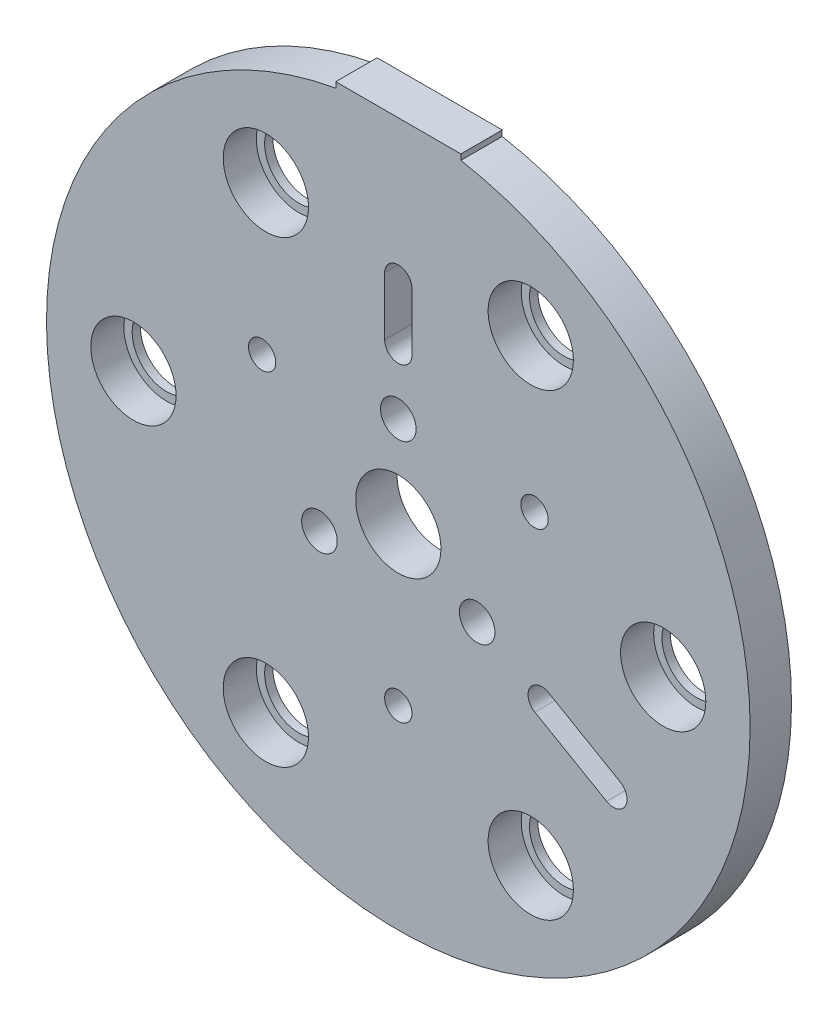
SolidWorks part; units mm, degrees
other "细节项目1"
other "细节项目2"
other "细节项目3"
ref_plane "前视基准面" through (0, 0, 0) normal (0, 0, 1) x (1, 0, 0)
ref_plane "上视基准面" through (0, 0, 0) normal (0, 1, 0) x (1, 0, 0)
ref_plane "右视基准面" through (0, 0, 0) normal (1, 0, 0) x (0, 0, -1)
other "Configuration Table"
sketch "草图1" plane through (0, 0, 0) normal (0, 0, 1) x (1, 0, 0)
  circle A0 centre (0, 0) radius 42.5
  point P0 (0, 0)
  point P19 (0, 0)
  dimension "D1" = 85
extrude "凸台-拉伸1" add sketch "草图1" against normal blind 5 contours A0
sketch "草图2" plane through (0, 0, 0) normal (0, 0, 1) x (1, 0, 0)
  line L0 (0, 0) -> (-32, 0) construction
  circle A1 centre (-32, 0) radius 5.15
  circle A2 centre (-16, 27.7128) radius 5.15
  circle A3 centre (16, 27.7128) radius 5.15
  circle A4 centre (32, 0) radius 5.15
  circle A5 centre (16, -27.7128) radius 5.15
  circle A6 centre (-16, -27.7128) radius 5.15
  point P17 (0, 0)
  dimension "D4" = 10.3
  dimension "D2" = 32
  dimension "D3" = 6
extrude "切除-拉伸1" cut sketch "草图2" against normal through all
sketch "草图3" plane through (0, 0, 0) normal (0, 0, 1) x (1, 0, 0)
  circle A0 centre (0, 0) radius 5.15
  dimension "D1" = 10.3
extrude "切除-拉伸2" cut sketch "草图3" against normal through all
sketch "草图4" plane through (0, 0, -5) normal (0, 0, -1) x (-1, 0, 0)
  circle A0 centre (-16, 27.7128) radius 5.15 construction
  circle A1 centre (-16, 27.7128) radius 5.15
  circle A2 centre (16, 27.7128) radius 5.15 construction
  circle A3 centre (16, 27.7128) radius 5.15
  circle A4 centre (32, 0) radius 5.15 construction
  circle A5 centre (32, 0) radius 5.15
  circle A6 centre (16, -27.7128) radius 5.15 construction
  circle A7 centre (16, -27.7128) radius 5.15
  circle A8 centre (-16, -27.7128) radius 5.15 construction
  circle A9 centre (-16, -27.7128) radius 5.15
  circle A10 centre (-32, 0) radius 5.15 construction
  circle A11 centre (-32, 0) radius 5.15
extrude "拉伸-薄壁1" add sketch "草图4" against normal blind 1 thin thin type one direction reverse wall 1
sketch "草图5" plane through (0, 0, -5) normal (0, 0, -1) x (-1, 0, 0)
  line L0 (0, 0) -> (-42.5, 0) construction
  line L1 (0, 0) -> (-36.8061, 21.25) construction
  circle A0 centre (0, 0) radius 42.5 construction
  circle A1 centre (-16.4545, 9.5) radius 1.65
  circle A2 centre (16.4545, 9.5) radius 1.65
  circle A3 centre (0, -19) radius 1.65
  point P16 (0, 0)
  dimension "D2" = 3.3
  dimension "D1" = 30
  dimension "D4" = 19
  dimension "D3" = 3
extrude "切除-拉伸3" cut sketch "草图5" against normal up to next
sketch "草图7" plane through (0, 0, -5) normal (0, 0, -1) x (-1, 0, 0)
  line L0 (0, 0) -> (-36.8061, -21.25) construction
  line L1 (-17.3205, -10) -> (-25.9808, -15) construction
  line L2 (-16.4955, -11.4289) -> (-25.1558, -16.4289)
  line L3 (-18.1455, -8.5711) -> (-26.8058, -13.5711)
  line L4 (0, 0) -> (-42.5, 0) construction
  circle A0 centre (0, 0) radius 42.5 construction
  arc A1 (-16.4955, -11.4289) -> (-18.1455, -8.5711) centre (-17.3205, -10) ccw
  arc A2 (-26.8058, -13.5711) -> (-25.1558, -16.4289) centre (-25.9808, -15) ccw
  point P8 (-21.6506, -12.5)
  dimension "D1" = 1.65
  dimension "D3" = 30
  dimension "D2" = 10
  dimension "D4" = 30
extrude "切除-拉伸4" cut sketch "草图7" against normal up to next
sketch "草图8" plane through (0, 0, 0) normal (0, 0, 1) x (1, 0, 0)
  line L0 (0, 0) -> (36.8061, -21.25) construction
  line L1 (18.1455, -8.5711) -> (26.8058, -13.5711) construction
  arc A3 (40.7925, -11.9256) -> (30.7241, -29.3646) centre (0, 0) cw
  circle A4 centre (0, 0) radius 42.5 construction
extrude "拉伸-薄壁2" [suppressed] add sketch "草图8" along normal blind 6 thin
ref_plane "基准面1" through (16.4955, -11.4289, 0) normal (-0.866, 0.5, 0) x (0, 0, 1)
sketch "草图9" plane through (16.4955, -11.4289, 0) normal (-0.866, 0.5, 0) x (0, 0, 1)
  line L0 (0, 1.65) -> (7.8846, 1.65) construction
  line L1 (0, 0) -> (0, 3.3) construction
  line L2 (0, 0) -> (0, 3.3) construction
  circle A0 centre (2.696, 1.65) radius 2.15
  point P6 (0, 1.65)
  dimension "D1" = 4.3
extrude "切除-拉伸5" [suppressed] cut sketch "草图9" against normal up to next
chamfer "倒角1" [suppressed] distance 4 angle 45
chamfer "倒角2" [suppressed] distance 4 angle 58
sketch "草图10" plane through (0, 0, -5) normal (0, 0, -1) x (-1, 0, 0)
  circle A0 centre (-9.5263, -5.5) radius 2.15
  circle A1 centre (0, 11) radius 2.15
  circle A2 centre (9.5263, -5.5) radius 2.15
  circle A4 centre (-9.5263, -5.5) radius 1.65 construction
  point P13 (0, 0)
  dimension "D1" = 4.3
  dimension "D3" = 3
extrude "切除-拉伸6" cut sketch "草图10" against normal up to next
sketch "草图11" plane through (0, 0, 0) normal (0, 0, 1) x (1, 0, 0)
  line L0 (0, 0) -> (0, 42.5) construction
  line L1 (0, 25.4578) -> (0, 18.4578) construction
  line L2 (1.65, 25.4578) -> (1.65, 18.4578)
  line L3 (-1.65, 25.4578) -> (-1.65, 18.4578)
  circle A0 centre (0, 0) radius 42.5 construction
  arc A1 (1.65, 25.4578) -> (-1.65, 25.4578) centre (0, 25.4578) ccw
  arc A2 (-1.65, 18.4578) -> (1.65, 18.4578) centre (0, 18.4578) ccw
  point P8 (0, 21.9578)
  dimension "D1" = 1.65
  dimension "D2" = 7
extrude "切除-拉伸7" cut sketch "草图11" against normal up to next
sketch "草图12" plane through (0, 0, 0) normal (0, 0, 1) x (1, 0, 0)
  line L0 (0, 42.5) -> (0, 0) construction
  arc A0 (-11.8308, 40.8201) -> (11.8308, 40.8201) centre (0, 0) cw
  circle A1 centre (0, 0) radius 42.5 construction
extrude "拉伸-薄壁3" [suppressed] add sketch "草图12" along normal blind 10 thin
sketch "草图14" plane through (0, 0, -5) normal (0, 0, -1) x (-1, 0, 0)
  line L0 (-7.5, 42.5) -> (7.5, 42.5)
  line L1 (0, 42.5) -> (0, 0) construction
  circle A0 centre (0, 0) radius 42.5 construction
  circle A1 centre (0, 0) radius 42.5 construction
  dimension "D1" = 15
extrude "拉伸-薄壁4" [suppressed] add sketch "草图14" against normal blind 15 thin
sketch "草图13" plane through (0, 0, 0) normal (0, 1, 0) x (1, 0, 0)
  line L0 (0, 0) -> (0, -3) construction
  line L1 (-42.5, 0) -> (42.5, 0) construction
  circle A0 centre (0, -3) radius 1.65
  dimension "D1" = 3.3
  dimension "D2" = 3
extrude "切除-拉伸8" [suppressed] cut sketch "草图13" along normal through all
chamfer "倒角3" [suppressed] distance 8 angle 45
sketch "草图15" plane through (0, 0, 0) normal (0, 0, 1) x (1, 0, 0)
  circle A9 centre (0, -19) radius 1.65 construction
  circle A12 centre (-16.4545, 9.5) radius 1.65 construction
  circle A14 centre (16.4545, 9.5) radius 1.65 construction
  circle A15 centre (0, -19) radius 1.65
  circle A17 centre (-16.4545, 9.5) radius 1.65
  circle A18 centre (16.4545, 9.5) radius 1.65
extrude "拉伸-薄壁5" [suppressed] add sketch "草图15" along normal blind 6 thin
chamfer "倒角4" [suppressed] distance 2 angle 73
chamfer "倒角5" [suppressed] distance 0.4 angle 45
sketch "草图17" plane through (0, 0, -5) normal (0, 0, -1) x (-1, 0, 0)
  line L0 (-7.5562, 42.5) -> (7.5562, 42.5)
  line L1 (0, 0) -> (0, 44.4396) construction
  circle A0 centre (0, 0) radius 42.5 construction
  point P7 (0, 0)
  point P8 (-7.5562, 42.5)
extrude "拉伸-薄壁6" add sketch "草图17" against normal up to surface (5 mm away) thin
